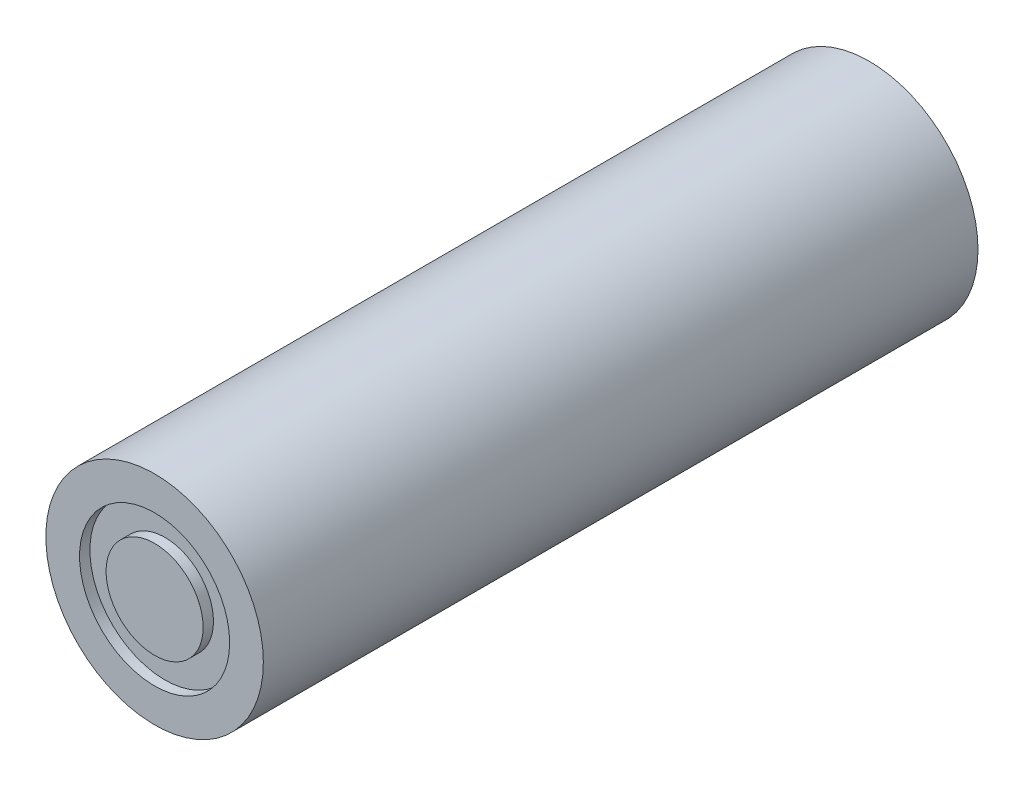
SolidWorks part; units mm, degrees
ref_plane "Front Plane" through (0, 0, 0) normal (0, 0, 1) x (1, 0, 0)
ref_plane "Top Plane" through (0, 0, 0) normal (0, 1, 0) x (1, 0, 0)
ref_plane "Right Plane" through (0, 0, 0) normal (1, 0, 0) x (0, 0, -1)
sketch "Sketch1" plane through (0, 0, 0) normal (0, 0, 1) x (1, 0, 0)
  circle A0 centre (0, 0) radius 10.675
  dimension "D1" = 21.35
extrude "Boss-Extrude1" add sketch "Sketch1" along normal mid plane 70.15
sketch "Sketch2" plane through (0, 0, 35.075) normal (0, 0, 1) x (1, 0, 0)
  circle A0 centre (0, 0) radius 7.366
  circle A1 centre (0, 0) radius 4.7625
  dimension "D1" = 9.525
  dimension "D2" = 14.732
extrude "Cut-Extrude1" cut sketch "Sketch2" against normal blind 1.016
